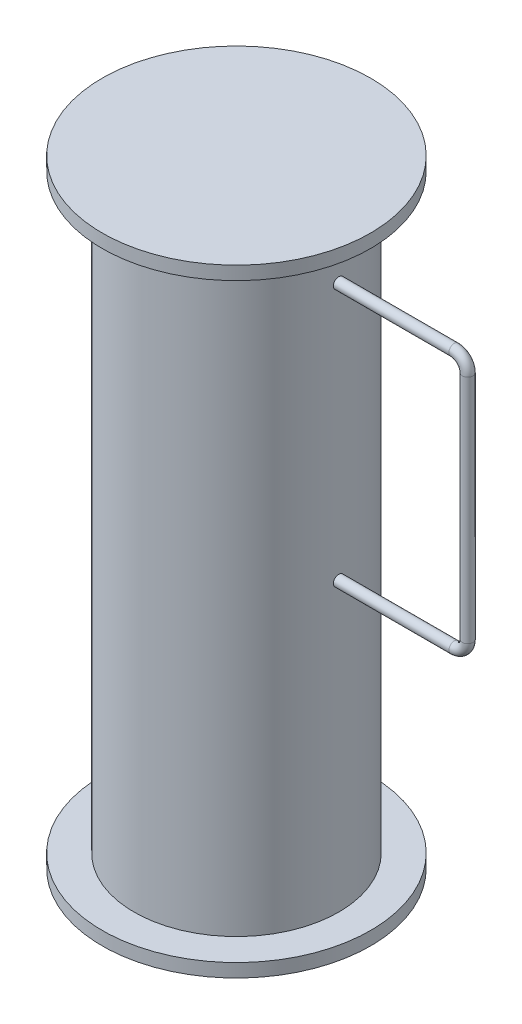
SolidWorks part; units mm, degrees
ref_plane "前基準面" through (0, 0, 0) normal (0, 0, 1) x (1, 0, 0)
ref_plane "上基準面" through (0, 0, 0) normal (0, 1, 0) x (1, 0, 0)
ref_plane "右基準面" through (0, 0, 0) normal (1, 0, 0) x (0, 0, -1)
sketch "草圖1" plane through (0, 0, 0) normal (0, 0, 1) x (1, 0, 0)
  line L0 (0, 0) -> (0, 230) construction
  line L1 (0, 230) -> (50, 230)
  line L2 (50, 230) -> (50, 225)
  line L3 (50, 225) -> (38.15, 225)
  line L4 (38.15, 225) -> (38.15, 5)
  line L5 (0, 0) -> (50, 0)
  line L6 (50, 0) -> (50, 5)
  line L7 (50, 5) -> (38.15, 5)
  line L8 (33.15, 225) -> (33.15, 5)
  line L9 (33.15, 225) -> (0, 225)
  line L10 (33.15, 5) -> (0, 5)
  dimension "D1" = 5
  dimension "D2" = 5
  dimension "D3" = 100
  dimension "D4" = 76.3
  dimension "D5" = 5
  dimension "D6" = 230
revolve "旋轉1" add sketch "草圖1" angle 360 about L0
sketch "草圖2" plane through (0, 0, 0) normal (0, 0, 1) x (1, 0, 0)
  line L0 (0, 208) -> (81.15, 208)
  line L1 (38.15, 5) -> (38.15, 225) construction
  line L2 (86.15, 203) -> (86.15, 117)
  line L3 (81.15, 112) -> (0, 112)
  line L4 (50, 230) -> (-50, 230) construction
  arc A0 (86.15, 117) -> (81.15, 112) centre (81.15, 117) cw
  arc A1 (81.15, 208) -> (86.15, 203) centre (81.15, 203) cw
  point P10 (86.15, 112)
  point P13 (86.15, 208)
  dimension "D4" = 5
  dimension "D1" = 96
  dimension "D2" = 48
  dimension "D3" = 22
sketch "草圖3" plane through (0, 0, 0) normal (1, 0, 0) x (0, 0, -1)
  circle A0 centre (0, 208) radius 2
  dimension "D1" = 4
sweep "掃出1" add profiles "草圖3" path "草圖2"
sketch "草圖4" plane through (0, 0, 0) normal (0, 0, 1) x (1, 0, 0)
  line L0 (-38.15, 200) -> (-48.15, 200)
  line L1 (-48.15, 180) -> (-38.15, 180)
  line L2 (-38.15, 225) -> (-38.15, 5) construction
  line L3 (50, 230) -> (-50, 230) construction
  arc A0 (-48.15, 200) -> (-48.15, 180) centre (-48.15, 190) ccw
  dimension "D3" = 10
  dimension "D1" = 20
  dimension "D2" = 40
sweep "掃出2" add path "草圖4" circular profile diameter 4 parameters "D3"=4
